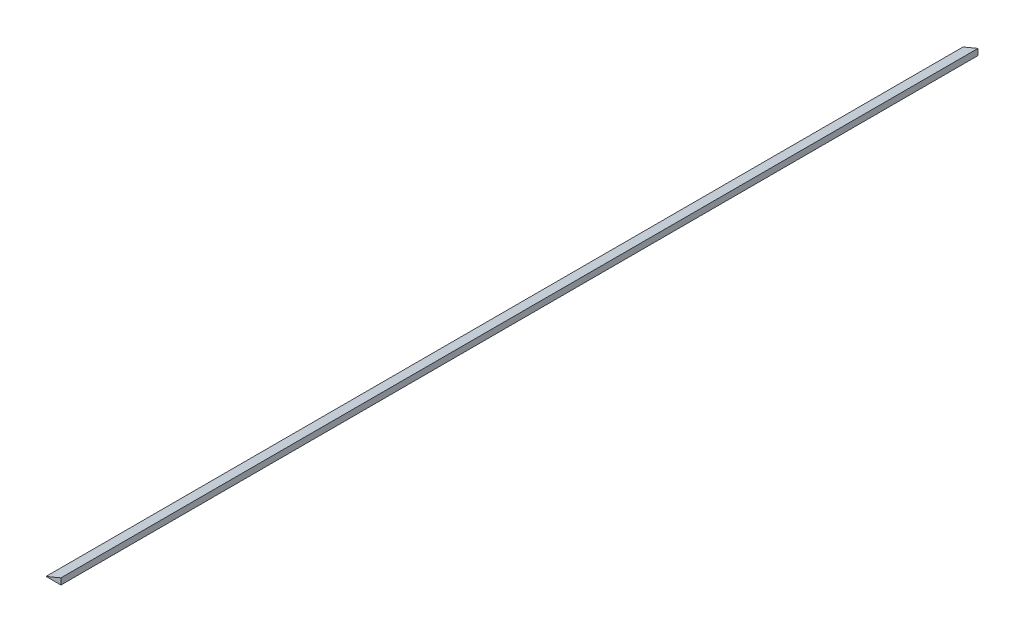
SolidWorks part; units mm, degrees
ref_plane "Front Plane" through (0, 0, 0) normal (0, 0, 1) x (1, 0, 0)
ref_plane "Top Plane" through (0, 0, 0) normal (0, 1, 0) x (1, 0, 0)
ref_plane "Right Plane" through (0, 0, 0) normal (1, 0, 0) x (0, 0, -1)
sketch "Sketch1" plane through (0, 0, 0) normal (0, 0, 1) x (1, 0, 0)
  line L0 (0, 0) -> (19.05, 0)
  line L1 (19.05, 0) -> (19.05, 7.9375)
  line L2 (19.05, 7.9375) -> (0, 0)
  dimension "D1" = 19.05
  dimension "D2" = 7.9375
extrude "Boss-Extrude1" add sketch "Sketch1" along normal blind 1168.4
